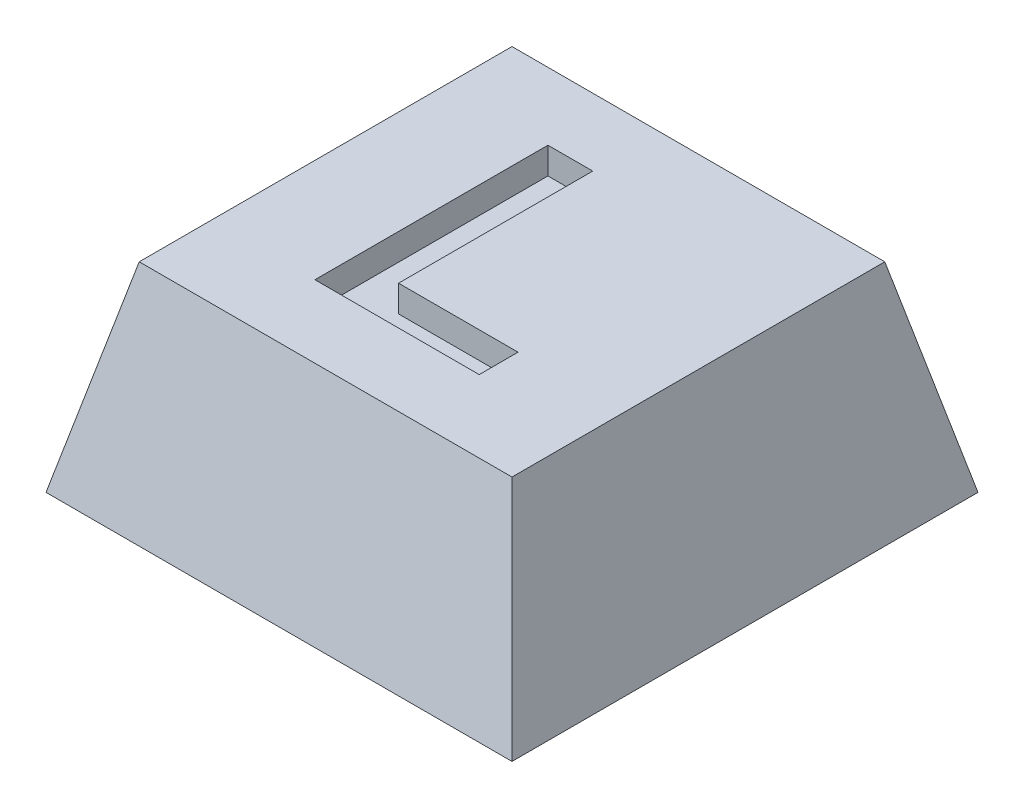
SolidWorks part; units mm, degrees
ref_plane "Front Plane" through (0, 0, 0) normal (0, 0, 1) x (1, 0, 0)
ref_plane "Top Plane" through (0, 0, 0) normal (0, 1, 0) x (1, 0, 0)
ref_plane "Right Plane" through (0, 0, 0) normal (1, 0, 0) x (0, 0, -1)
sketch "Sketch1" plane through (0, 0, 0) normal (0, 1, 0) x (1, 0, 0)
  line L1 (0, 0) -> (7, 0)
  line L2 (0, 0) -> (0, 7)
  line L3 (0, 7) -> (7, 7)
  line L4 (7, 0) -> (7, 7)
  dimension "D1" = 7
  dimension "D2" = 7
extrude "Boss-Extrude1" add sketch "Sketch1" along normal blind 3
sketch "Sketch2" plane through (0, 0, 0) normal (0, 0, 1) x (1, 0, 0)
  line L0 (0, 0) -> (0.7, 3)
  line L1 (0, 3) -> (7, 3) construction
  line L2 (0.7, 3) -> (0, 3)
  line L3 (0, 3) -> (0, 0)
  line L4 (7, 0) -> (6.3, 3)
  line L5 (6.3, 3) -> (7, 3)
  line L6 (7, 3) -> (7, 0)
  dimension "D1" = 0.7
  dimension "D2" = 0.7
extrude "Cut-Extrude1" cut sketch "Sketch2" against normal blind 7
sketch "Sketch3" plane through (0, 0, 0) normal (1, 0, 0) x (0, 0, -1)
  line L0 (0, 0) -> (0.7, 3)
  line L1 (7, 3) -> (0, 3) construction
  line L2 (0.7, 3) -> (0, 3)
  line L3 (0, 3) -> (0, 0)
  line L4 (7, 3) -> (6.3, 3)
  line L5 (6.3, 3) -> (7, 0)
  line L6 (7, 3) -> (7, 0)
  dimension "D1" = 0.7
  dimension "D2" = 0.7
extrude "Cut-Extrude2" cut sketch "Sketch3" along normal blind 11
sketch "Sketch4" plane through (0, 0, 0) normal (0, -1, 0) x (1, 0, 0)
  line L0 (3.5, 0) -> (3.5, -7) construction
  line L1 (0, 0) -> (7, 0) construction
  line L2 (7, -7) -> (0, -7) construction
  line L3 (0, -3.5) -> (7, -3.5) construction
  line L4 (0, -7) -> (0, 0) construction
  line L5 (7, 0) -> (7, -7) construction
  circle A0 centre (3.5, -3.5) radius 1.8
  dimension "D1" = 3.6
extrude "Cut-Extrude3" cut sketch "Sketch4" against normal blind 0.8
sketch "Sketch5" plane through (0, 3, 0) normal (0, 1, 0) x (1, 0, 0)
  text T0 "L" font "Arial" height 3.5
extrude "Cut-Extrude4" cut sketch "Sketch5" against normal blind 0.4
